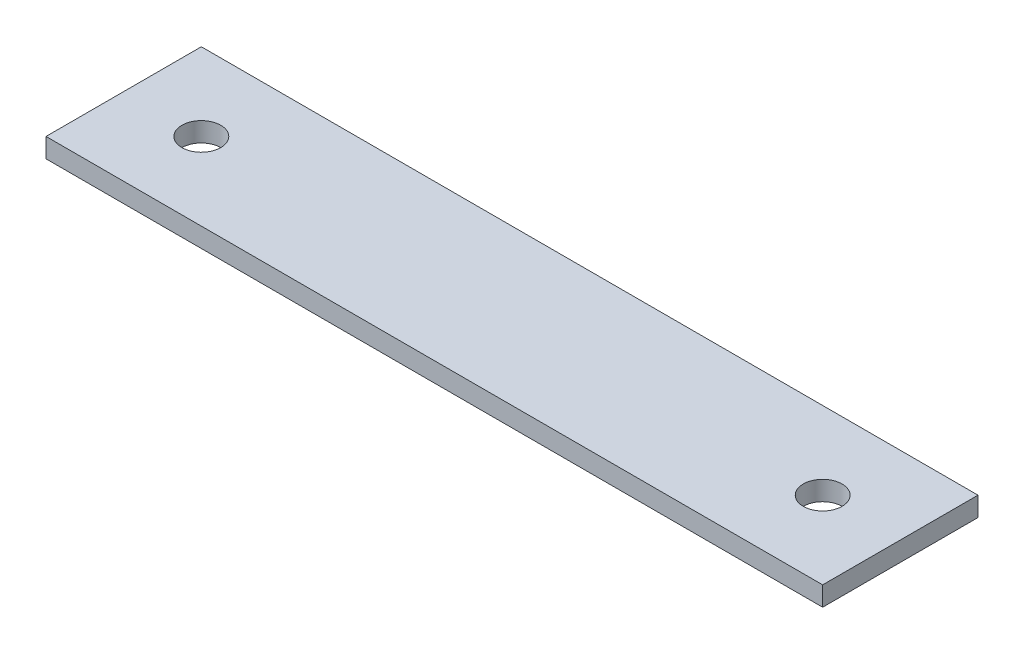
SolidWorks part; units mm, degrees
material "6061 Alloy"
ref_plane "Front Plane" through (0, 0, 0) normal (0, 0, 1) x (1, 0, 0)
ref_plane "Top Plane" through (0, 0, 0) normal (0, 1, 0) x (1, 0, 0)
ref_plane "Right Plane" through (0, 0, 0) normal (1, 0, 0) x (0, 0, -1)
sketch "Sketch1" plane through (0, 0, 0) normal (0, 1, 0) x (1, 0, 0)
  line L1 (0, 0) -> (127, 0)
  line L2 (0, 0) -> (0, 25.4)
  line L3 (0, 25.4) -> (127, 25.4)
  line L4 (127, 0) -> (127, 25.4)
  dimension "D1" = 25.4
  dimension "D2" = 127
extrude "Boss-Extrude1" add sketch "Sketch1" along normal blind 3.175 contours L3 L4 L1 L2
sketch "Sketch2" plane through (0, 3.175, 0) normal (0, 1, 0) x (1, 0, 0)
  line L0 (0, 25.4) -> (127, 25.4) construction
  line L1 (0, 0) -> (0, 25.4) construction
  circle A0 centre (12.7, 12.7) radius 3.175
  circle A1 centre (114.3, 12.7) radius 3.175
  dimension "D1" = 6.35
  dimension "D2" = 12.7
  dimension "D3" = 12.7
  dimension "D4" = 12.7
  dimension "D5" = 114.3
extrude "Cut-Extrude1" cut sketch "Sketch2" against normal blind 3.175
